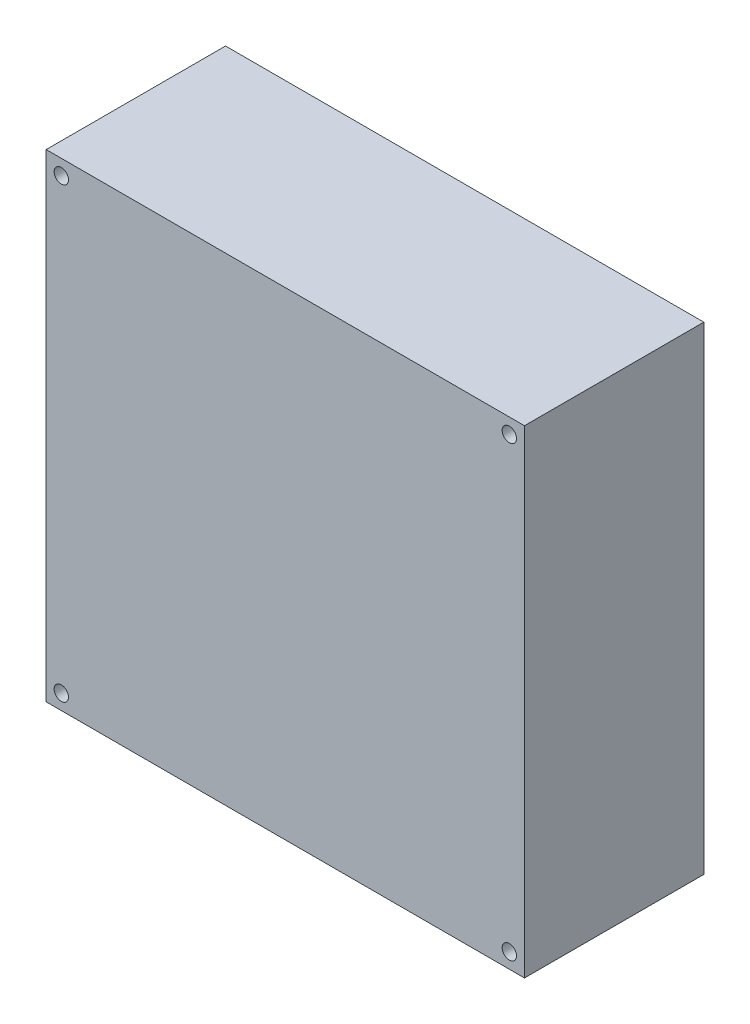
SolidWorks part; units mm, degrees
ref_plane "前视基准面" through (0, 0, 0) normal (0, 0, 1) x (1, 0, 0)
ref_plane "上视基准面" through (0, 0, 0) normal (0, 1, 0) x (1, 0, 0)
ref_plane "右视基准面" through (0, 0, 0) normal (1, 0, 0) x (0, 0, -1)
other "Configuration Table"
sketch "草图1" plane through (0, 0, 0) normal (0, 0, 1) x (1, 0, 0)
  line L1 (0, 0) -> (120, 0)
  line L2 (0, 0) -> (0, 120)
  line L3 (0, 120) -> (120, 120)
  line L4 (120, 0) -> (120, 120)
  dimension "D1" = 120
  dimension "D2" = 120
extrude "凸台-拉伸1" add sketch "草图1" along normal blind 45
sketch "草图2" plane through (0, 0, 45) normal (0, 0, 1) x (1, 0, 0)
  line L0 (60, 120) -> (60, -49880) construction
  line L1 (120, 120) -> (0, 120) construction
  line L2 (120, 60) -> (-49880, 60) construction
  line L3 (120, 0) -> (120, 120) construction
  line L5 (3.8, 3.8) -> (116.2, 3.8) construction
  line L6 (3.8, 3.8) -> (3.8, 116.2) construction
  line L7 (3.8, 116.2) -> (116.2, 116.2) construction
  line L8 (116.2, 3.8) -> (116.2, 116.2) construction
  line L9 (3.8, 3.8) -> (116.2, 116.2) construction
  line L10 (3.8, 116.2) -> (116.2, 3.8) construction
  circle A0 centre (3.8, 116.2) radius 1.8
  circle A1 centre (116.2, 116.2) radius 1.8
  circle A2 centre (116.2, 3.8) radius 1.8
  circle A3 centre (3.8, 3.8) radius 1.8
  point P4 (60, 120)
  point P9 (120, 60)
  point P10 (60, 60)
  point P25 (60, 60)
  dimension "D3" = 3.6
  dimension "D1" = 112.4
  dimension "D2" = 112.4
extrude "切除-拉伸1" cut sketch "草图2" against normal up to next
